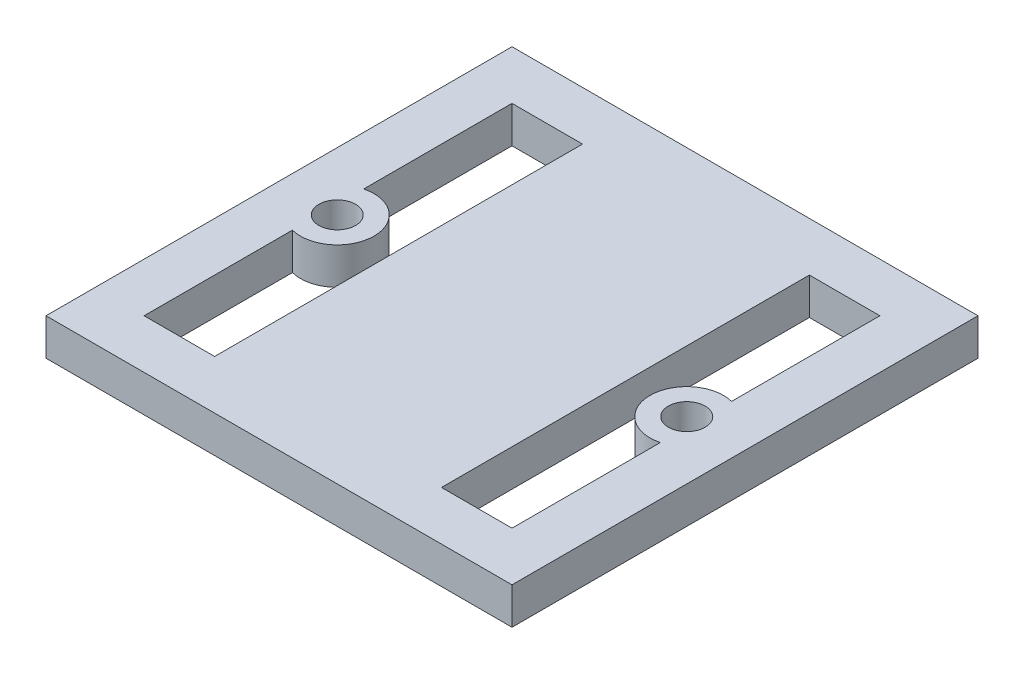
SolidWorks part; units mm, degrees
material "PET"
ref_plane "Front Plane" through (0, 0, 0) normal (0, 0, 1) x (1, 0, 0)
ref_plane "Top Plane" through (0, 0, 0) normal (0, 1, 0) x (1, 0, 0)
ref_plane "Right Plane" through (0, 0, 0) normal (1, 0, 0) x (0, 0, -1)
sketch "Sketch1" plane through (0, 0, 0) normal (0, 1, 0) x (1, 0, 0)
  line L0 (-15, -15) -> (-15, 15)
  line L1 (-19, -19) -> (19, -19)
  line L2 (-19, -19) -> (-19, 19)
  line L3 (-19, 19) -> (19, 19)
  line L4 (19, -19) -> (19, 19)
  line L5 (-19, -19) -> (19, 19) construction
  line L6 (-19, 19) -> (19, -19) construction
  line L7 (-6.25, -12.5) -> (6.25, -12.5)
  line L8 (-6.25, -12.5) -> (-6.25, 12.5)
  line L9 (-6.25, 12.5) -> (6.25, 12.5)
  line L10 (6.25, -12.5) -> (6.25, 12.5)
  line L11 (-6.25, -12.5) -> (6.25, 12.5) construction
  line L12 (-6.25, 12.5) -> (6.25, -12.5) construction
  line L13 (-15, 15) -> (15, 15)
  line L16 (15, -15) -> (15, 15)
  line L17 (-15, -15) -> (15, -15)
  line L18 (-9.25, -15.5) -> (-9.25, 15.5)
  line L19 (-9.25, 15.5) -> (9.25, 15.5)
  line L20 (9.25, -15.5) -> (9.25, 15.5)
  line L21 (-9.25, -15.5) -> (9.25, -15.5)
  circle A0 centre (-14.25, 0) radius 1.5
  circle A1 centre (14.25, 0) radius 1.5
  circle A2 centre (-14.25, 0) radius 3
  circle A3 centre (14.25, 0) radius 3
  point P0 (0, 0)
  point P6 (0, 0)
  dimension "D1" = 38
  dimension "D2" = 38
  dimension "D3" = 12.5
  dimension "D4" = 25
extrude "Boss-Extrude1" add sketch "Sketch1" along normal blind 3 contours L1 L4 L3 L2 A3 L16 L17 L20 L21 L18 L0 A2 L13 L19 | L17 L20 L13 L18 L10 L7 L8 L9 | L7 L10 L9 L8 | L0 A2 A0 | L0 A2 A0 | L16 A3 A1 | L16 A3 A1 | L18 L21 L20 L17 | L13 L20 L19 L18
